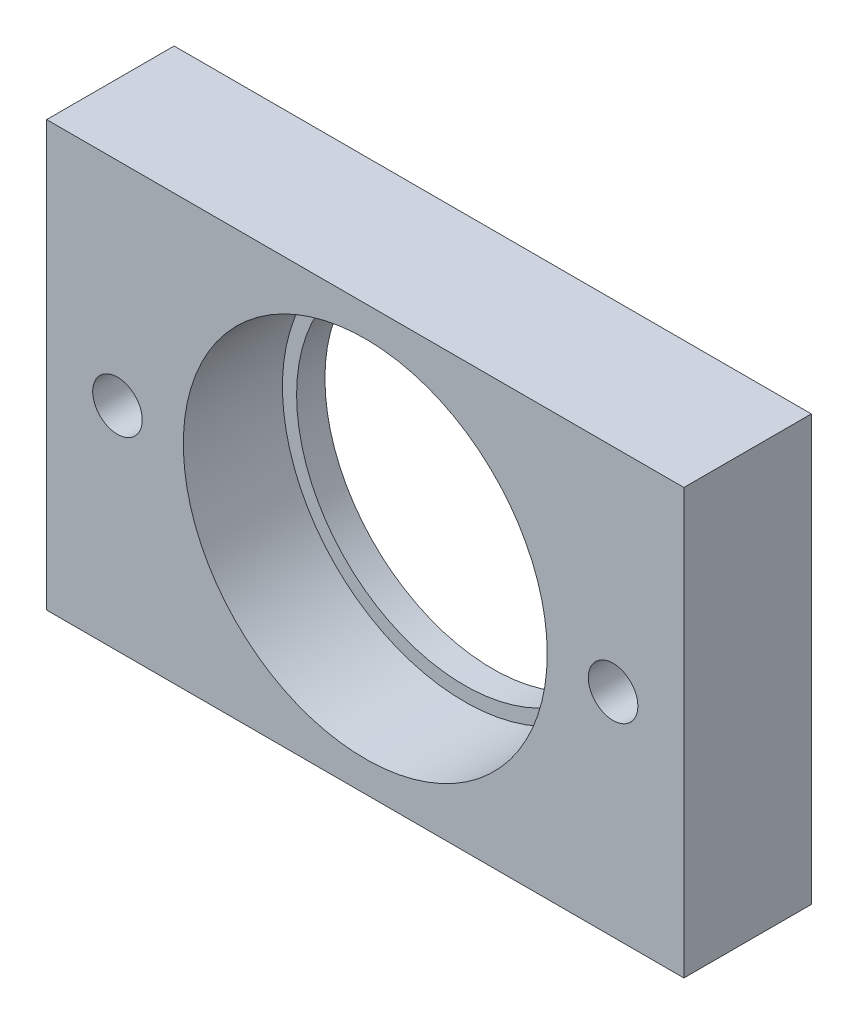
SolidWorks part; units mm, degrees
ref_plane "Ebene vorne" through (0, 0, 0) normal (0, 0, 1) x (1, 0, 0)
ref_plane "Ebene oben" through (0, 0, 0) normal (0, 1, 0) x (1, 0, 0)
ref_plane "Ebene rechts" through (0, 0, 0) normal (1, 0, 0) x (0, 0, -1)
sketch "Skizze1" plane through (0, 0, 0) normal (0, 0, 1) x (1, 0, 0)
  line L0 (0, 30.7034) -> (0, -36.0719) construction
  line L1 (-22.5, 15) -> (22.5, 15)
  line L2 (-22.5, 15) -> (-22.5, -15)
  line L3 (-22.5, -15) -> (22.5, -15)
  line L4 (22.5, 15) -> (22.5, -15)
  line L5 (-46.916, 0) -> (42.9512, 0) construction
  circle A0 centre (0, 0) radius 11.85
  circle A1 centre (-17.5, 0) radius 1.75
  circle A2 centre (17.5, 0) radius 1.75
  dimension "D3" = 23.7
  dimension "D4" = 3.5
  dimension "D1" = 45
  dimension "D2" = 30
  dimension "D5" = 35
extrude "Aufsatz-Linear austragen1" add sketch "Skizze1" along normal blind 9
sketch "Skizze3" plane through (0, 0, 9) normal (0, 0, 1) x (1, 0, 0)
  circle A2 centre (0, 0) radius 12.85
  circle A3 centre (0, 0) radius 12.85
  dimension "D1" = 1
extrude "Schnitt-Linear austragen1" cut sketch "Skizze3" against normal blind 7
